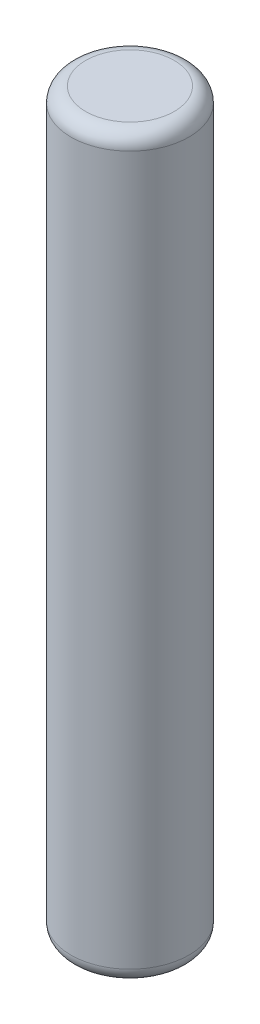
SolidWorks part; units mm, degrees
ref_plane "Front Plane" through (0, 0, 0) normal (0, 0, 1) x (1, 0, 0)
ref_plane "Top Plane" through (0, 0, 0) normal (0, 1, 0) x (1, 0, 0)
ref_plane "Right Plane" through (0, 0, 0) normal (1, 0, 0) x (0, 0, -1)
sketch "Sketch1" plane through (0, 0, 0) normal (0, 1, 0) x (1, 0, 0)
  circle A0 centre (0, 0) radius 4
  dimension "D1" = 8
extrude "Boss-Extrude1" add sketch "Sketch1" along normal blind 50
fillet "Fillet1" radius 1 1 edges at (0, 50, 4)
fillet "Fillet2" radius 1 1 edges at (0, 0, 4)
scale "Scale1" scale about centroid uniform scaling yes scale factor 0.7
